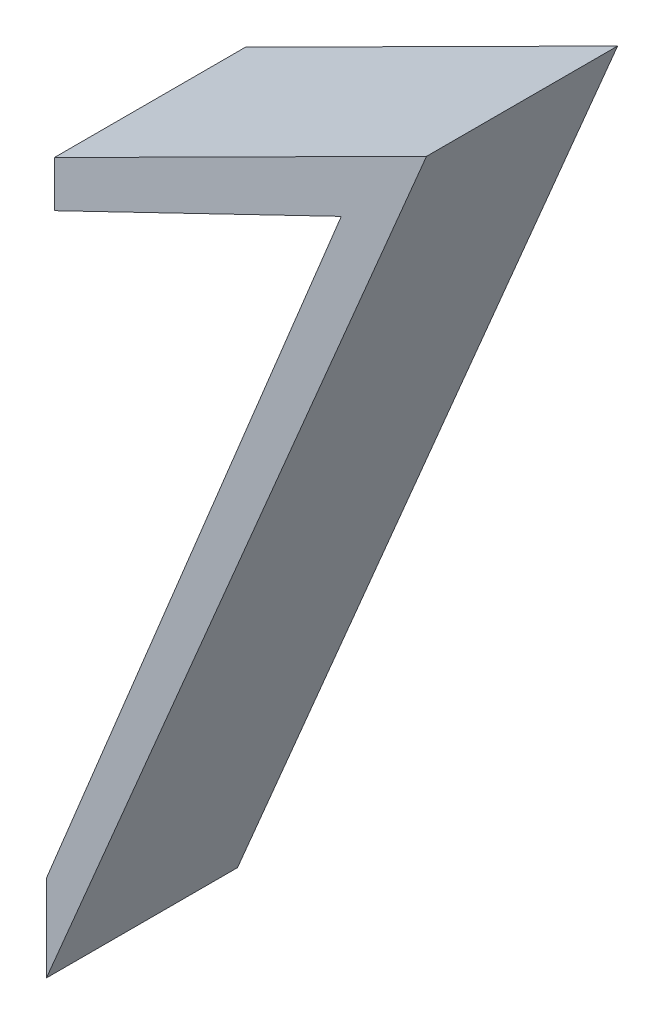
SolidWorks part; units mm, degrees
ref_plane "Front Plane" through (0, 0, 0) normal (0, 0, 1) x (1, 0, 0)
ref_plane "Top Plane" through (0, 0, 0) normal (0, 1, 0) x (1, 0, 0)
ref_plane "Right Plane" through (0, 0, 0) normal (1, 0, 0) x (0, 0, -1)
sketch "Sketch1" plane through (0, 0, 0) normal (0, 0, 1) x (1, 0, 0)
  line L0 (-6.8119, 24.428) -> (2.9252, 29.3235)
  line L1 (2.9252, 29.3235) -> (-7.0205, 5.7327)
  line L2 (-7.0205, 5.7327) -> (-7.0205, 7.9939)
  line L3 (-7.0205, 7.9939) -> (0.696, 26.8483)
  line L4 (0.696, 26.8483) -> (-6.8119, 23.2234)
  line L5 (-6.8119, 23.2234) -> (-6.8119, 24.428)
  point P2 (-5.0532, 7.9939)
  point P7 (-5.4027, 10.4092)
  point P8 (0.696, 26.8483)
  point P9 (2.9252, 29.3235)
  point P10 (-7.0205, 7.9939)
  point P11 (-7.0205, 5.7327)
extrude "Boss-Extrude1" add sketch "Sketch1" along normal blind 5
